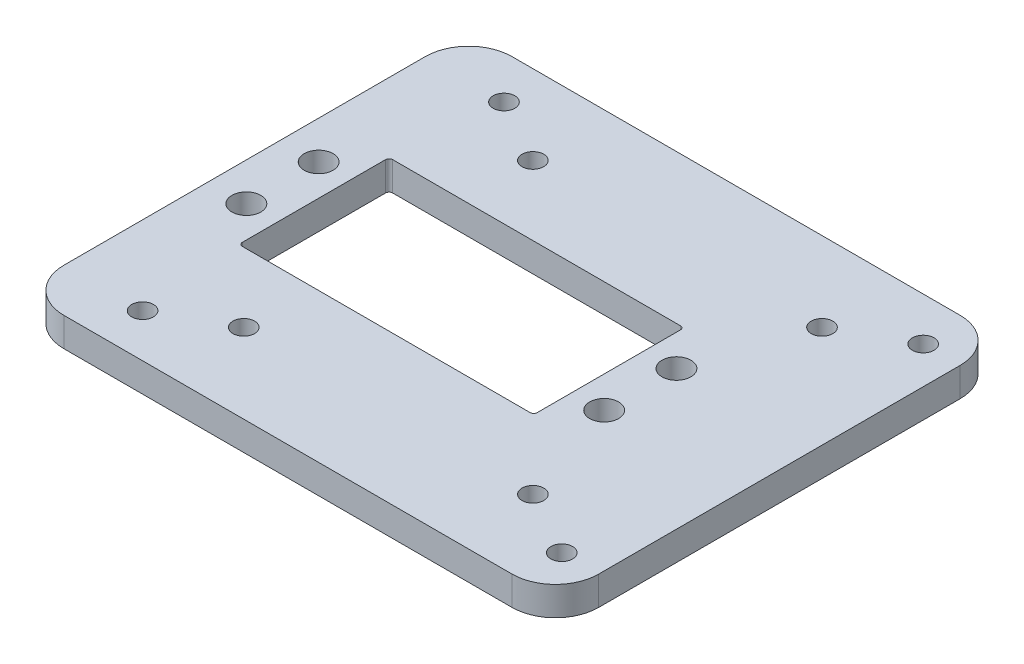
SolidWorks part; units mm, degrees
material "Thornel Mat VMA"
ref_plane "前视基准面" through (0, 0, 0) normal (0, 0, 1) x (1, 0, 0)
ref_plane "上视基准面" through (0, 0, 0) normal (0, 1, 0) x (1, 0, 0)
ref_plane "右视基准面" through (0, 0, 0) normal (1, 0, 0) x (0, 0, -1)
other "Configuration Table"
sketch "草图1" plane through (0, 0, 0) normal (0, 1, 0) x (1, 0, 0)
  line L0 (0, 0) -> (0, 29.6725) construction
  line L1 (-30, -31) -> (30, -31)
  line L2 (-30, -31) -> (-30, 31)
  line L3 (-30, 31) -> (30, 31)
  line L4 (30, -31) -> (30, 31)
  line L5 (-30, -31) -> (30, 31) construction
  line L6 (-30, 31) -> (30, -31) construction
  line L11 (-15.5388, -16.0567) -> (15.4817, 15.9977) construction
  line L12 (9.89, 0) -> (9.89, 37.58) construction
  line L13 (-20.4, -10.4) -> (20.4, -10.4)
  line L14 (-20.4, -10.4) -> (-20.4, 10.4)
  line L15 (-20.4, 10.4) -> (20.4, 10.4)
  line L16 (20.4, -10.4) -> (20.4, 10.4)
  line L17 (-20.4, -10.4) -> (20.4, 10.4) construction
  line L18 (-20.4, 10.4) -> (20.4, -10.4) construction
  line L19 (0, 0) -> (43.0948, 0) construction
  line L20 (30, 31) -> (44, 31)
  line L21 (44, 31) -> (44, -31)
  line L22 (30, -31) -> (44, -31)
  circle A0 centre (24.75, 5) radius 2
  circle A1 centre (24.75, -5) radius 2
  circle A2 centre (-24.75, -5) radius 2
  circle A3 centre (-24.75, 5) radius 2
  circle A8 centre (-19.11, 25) radius 1.5
  circle A9 centre (-19.11, -25) radius 1.5
  circle A10 centre (38.89, -25) radius 1.5
  circle A11 centre (38.89, 25) radius 1.5
  circle A12 centre (-10.11, 20) radius 1.5
  circle A13 centre (29.89, 20) radius 1.5
  circle A14 centre (29.89, -20) radius 1.5
  circle A15 centre (-10.11, -20) radius 1.5
  point P0 (0, 0)
  point P6 (0, 0)
  point P13 (0, 0)
  point P38 (44, 0)
  dimension "D5" = 4
  dimension "D8" = 9.89
  dimension "D7" = 49.5
  dimension "D9" = 3
  dimension "D10" = 25
  dimension "D13" = 3
  dimension "D14" = 40
  dimension "D15" = 40
  dimension "D1" = 60
  dimension "D2" = 62
  dimension "D3" = 40.8
  dimension "D4" = 20.8
  dimension "D6" = 5
  dimension "D11" = 29
  dimension "D12" = 14
extrude "凸台-拉伸1" add sketch "草图1" along normal blind 4 contours L1 L4 L3 L2 A3 A2 L16 L13 L14 L15 A0 A1 A8 A9 | L4 L22 L21 L20 A10 A11
fillet "圆角1" radius 0.5 4 edges at (20.4, 2, 10.4) (-20.4, 2, 10.4) (20.4, 2, -10.4) (-20.4, 2, -10.4)
fillet "圆角2" radius 6 4 edges at (44, 2, -31) (44, 2, 31) (-30, 2, 31) (-30, 2, -31)
